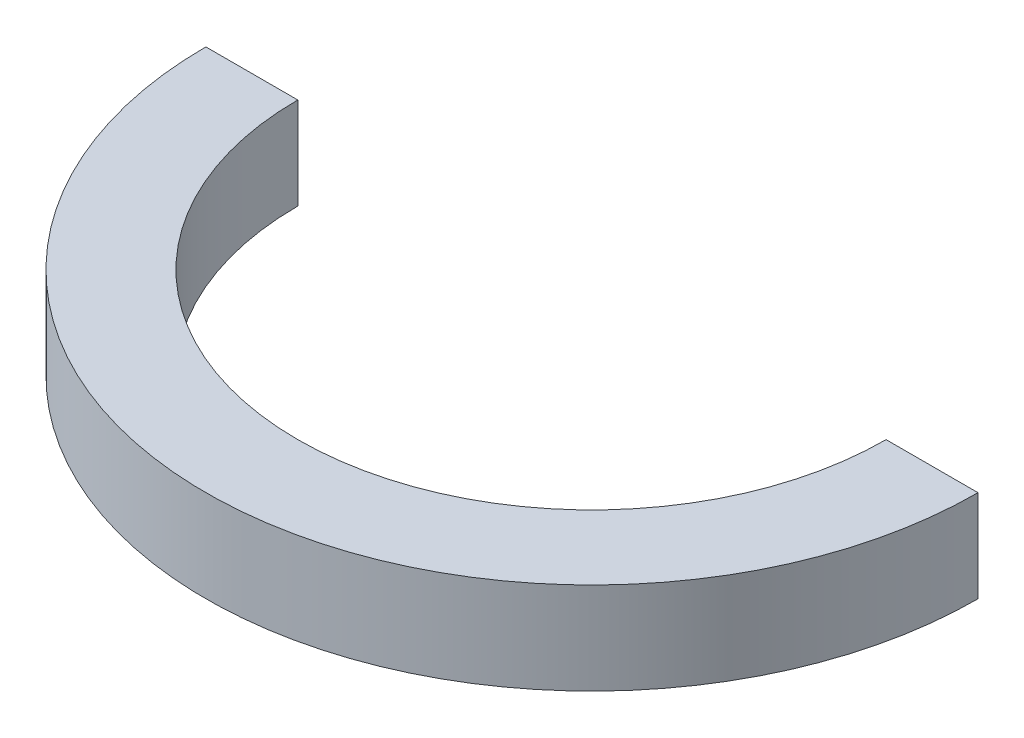
SolidWorks part; units mm, degrees
ref_plane "Спереди" through (0, 0, 0) normal (0, 0, 1) x (1, 0, 0)
ref_plane "Сверху" through (0, 0, 0) normal (0, 1, 0) x (1, 0, 0)
ref_plane "Справа" through (0, 0, 0) normal (1, 0, 0) x (0, 0, -1)
other "Configuration Table"
sketch "Эскиз1" plane through (0, 0, 0) normal (0, 1, 0) x (1, 0, 0)
  arc A0 (-32, 0) -> (32, 0) centre (0, 0) ccw
extrude "Вытянуть-Тонкостенный1" add sketch "Эскиз1" along normal blind 10 thin
